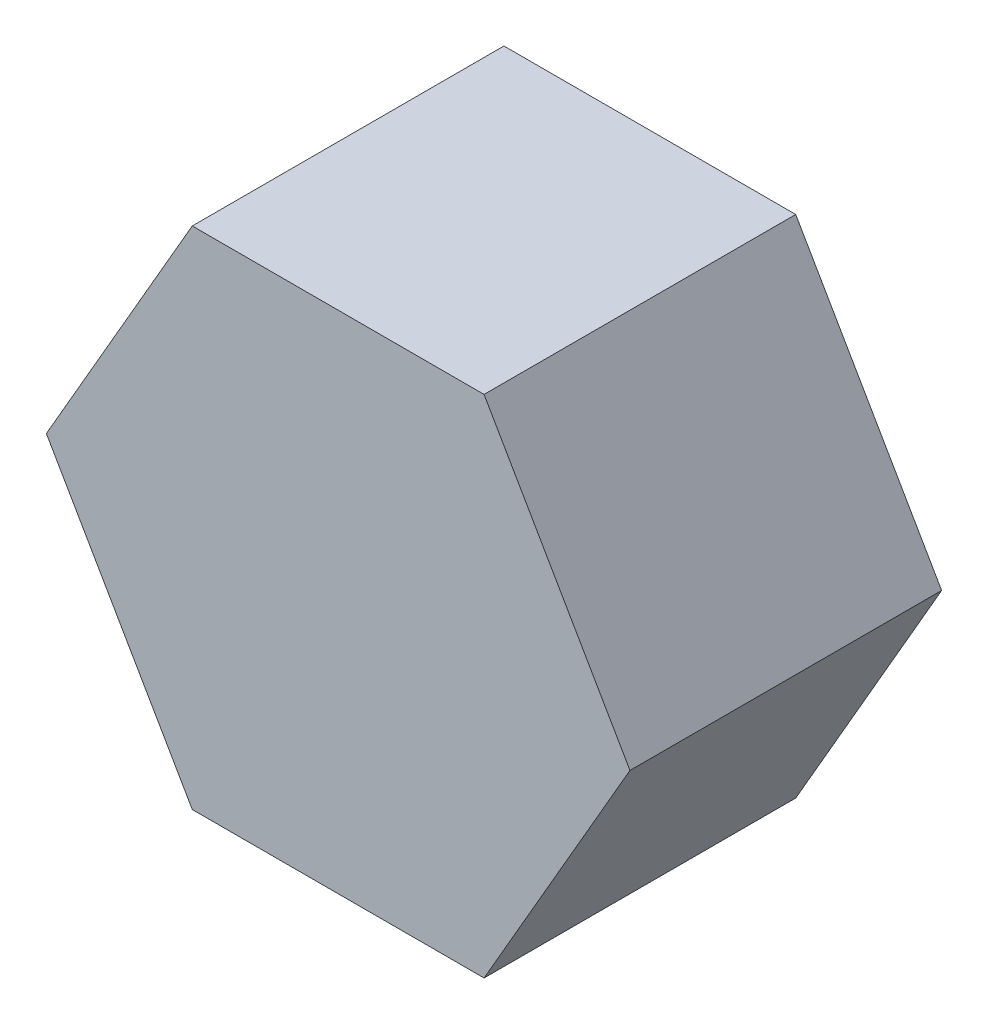
SolidWorks part; units mm, degrees
ref_plane "前视基准面" through (0, 0, 0) normal (0, 0, 1) x (1, 0, 0)
ref_plane "上视基准面" through (0, 0, 0) normal (0, 1, 0) x (1, 0, 0)
ref_plane "右视基准面" through (0, 0, 0) normal (1, 0, 0) x (0, 0, -1)
other "Configuration Table"
sketch "草图1" plane through (0, 0, 0) normal (0, 0, 1) x (1, 0, 0)
  line L1 (13.856, 0) -> (6.928, 11.9996)
  line L2 (6.928, 11.9996) -> (-6.928, 11.9996)
  line L3 (-6.928, 11.9996) -> (-13.856, 0)
  line L4 (-13.856, 0) -> (-6.928, -11.9996)
  line L5 (-6.928, -11.9996) -> (6.928, -11.9996)
  line L6 (6.928, -11.9996) -> (13.856, 0)
  circle A0 centre (0, 0) radius 11.9996 construction
extrude "凸台-拉伸1" add sketch "草图1" along normal blind 14.8
sketch "草图2" plane through (0, 0, 0) normal (0, 0, 1) x (1, 0, 0)
  line L1 (13.856, 0) -> (6.928, 11.9996)
  line L2 (6.928, 11.9996) -> (-6.928, 11.9996)
  line L3 (-6.928, 11.9996) -> (-13.856, 0)
  line L4 (-13.856, 0) -> (-6.928, -11.9996)
  line L5 (-6.928, -11.9996) -> (6.928, -11.9996)
  line L6 (6.928, -11.9996) -> (13.856, 0)
  circle A0 centre (0, 0) radius 11.9996 construction
sketch "草图3" plane through (0, 0, 0) normal (0, 0, 1) x (1, 0, 0)
  circle A0 centre (0, 0) radius 7
